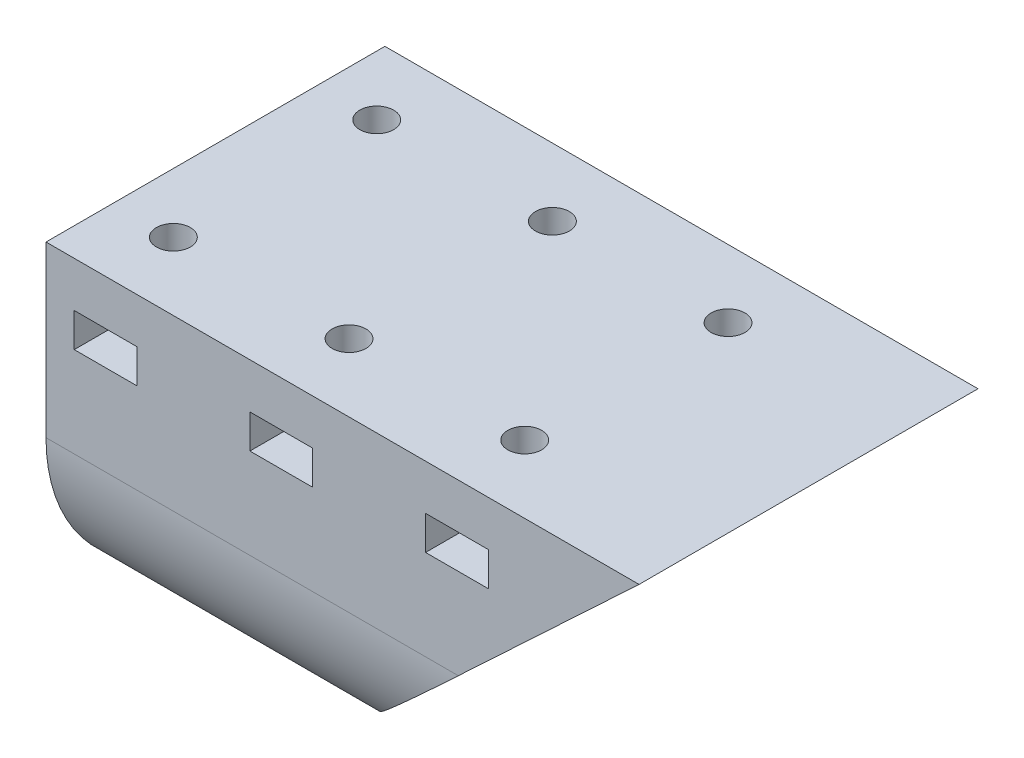
SolidWorks part; units mm, degrees
ref_plane "Front Plane" through (0, 0, 0) normal (0, 0, 1) x (1, 0, 0)
ref_plane "Top Plane" through (0, 0, 0) normal (0, 1, 0) x (1, 0, 0)
ref_plane "Right Plane" through (0, 0, 0) normal (1, 0, 0) x (0, 0, -1)
sketch "Sketch1" plane through (0, 0, 0) normal (1, 0, 0) x (0, 0, -1)
  line L0 (1.4916, 6.9937) -> (6.9937, 1.4916) construction
  line L1 (-6.9937, -1.4916) -> (-1.4916, -6.9937) construction
  line L2 (0, 0) -> (15, 0) construction
  circle A0 centre (0, 0) radius 15
  arc A5 (-6.9937, -1.4916) -> (1.4916, 6.9937) centre (0, 0) cw construction
  arc A6 (6.9937, 1.4916) -> (-1.4916, -6.9937) centre (0, 0) cw construction
  circle A7 centre (0, 0) radius 12.85
  point P14 (0, 0)
  dimension "D1" = 30
  dimension "D2" = 25.7
  dimension "D5" = 12
  dimension "D6" = 6
  dimension "D7" = 45
extrude "Boss-Extrude1" add sketch "Sketch1" along normal blind 2.5
sketch "Sketch2" plane through (2.5, 0, 0) normal (1, 0, 0) x (0, 0, -1)
  line L0 (-15, 15) -> (15, 15)
  line L4 (15, 15) -> (15, 0)
  line L5 (-15, 0) -> (-15, 15)
  circle A1 centre (0, 0) radius 12.8
  arc A2 (15, 0) -> (-15, 0) centre (0, 0) cw
  point P6 (0, 15)
  dimension "D1" = 25.6
  dimension "D2" = 15
  dimension "D3" = 30
extrude "Boss-Extrude2" add sketch "Sketch2" along normal blind 50 and the other way up to surface (2.5 mm away) other way up to face at (0, 0, -12.85)
sketch "Sketch3" plane through (0, 0, 0) normal (0, 0, 1) x (1, 0, 0)
  line L0 (52.5, 15) -> (20.5, -15)
  line L4 (20.5, -15) -> (52.5, -15)
  line L5 (52.5, -15) -> (52.5, 15)
  line L8 (0, -15) -> (52.5, -15) construction
  dimension "D2" = 20.5
extrude "Cut-Extrude1" cut sketch "Sketch3" against normal through all both and the other way through all
sketch "Sketch4" plane through (0, 0, 15) normal (0, 0, 1) x (1, 0, 0)
  line L1 (2.5, 11) -> (8.05, 11)
  line L2 (2.5, 11) -> (2.5, 8)
  line L3 (2.5, 8) -> (8.05, 8)
  line L4 (8.05, 11) -> (8.05, 8)
  line L5 (18.05, 11) -> (23.6, 11)
  line L6 (18.05, 11) -> (18.05, 8)
  line L7 (18.05, 8) -> (23.6, 8)
  line L8 (23.6, 11) -> (23.6, 8)
  line L9 (33.6, 11) -> (39.15, 11)
  line L10 (33.6, 11) -> (33.6, 8)
  line L11 (33.6, 8) -> (39.15, 8)
  line L12 (39.15, 11) -> (39.15, 8)
  line L14 (0, 0) -> (0, 15) construction
  dimension "D1" = 5.55
  dimension "D2" = 3
  dimension "D3" = 2.5
  dimension "D4" = 8
  dimension "D5" = 10
  dimension "D6" = 10
extrude "Cut-Extrude2" cut sketch "Sketch4" against normal blind 9
sketch "Sketch5" plane through (0, 15, 0) normal (0, 1, 0) x (1, 0, 0)
  line L0 (0, -15) -> (0, 15) construction
  circle A0 centre (5.275, -9) radius 1.5
  circle A1 centre (20.825, -9) radius 1.5
  circle A2 centre (36.375, -9) radius 1.5
  dimension "D1" = 3
  dimension "D2" = 15.55
  dimension "D3" = 15.55
  dimension "D4" = 9
  dimension "D5" = 5.275
extrude "Cut-Extrude3" cut sketch "Sketch5" against normal up to surface (7 mm away) up to face at (20.825, 8, 12.496)
mirror "Mirror1" about plane through (0, 0, 0) normal (0, 0, 1) of "Cut-Extrude2", "Cut-Extrude3"
